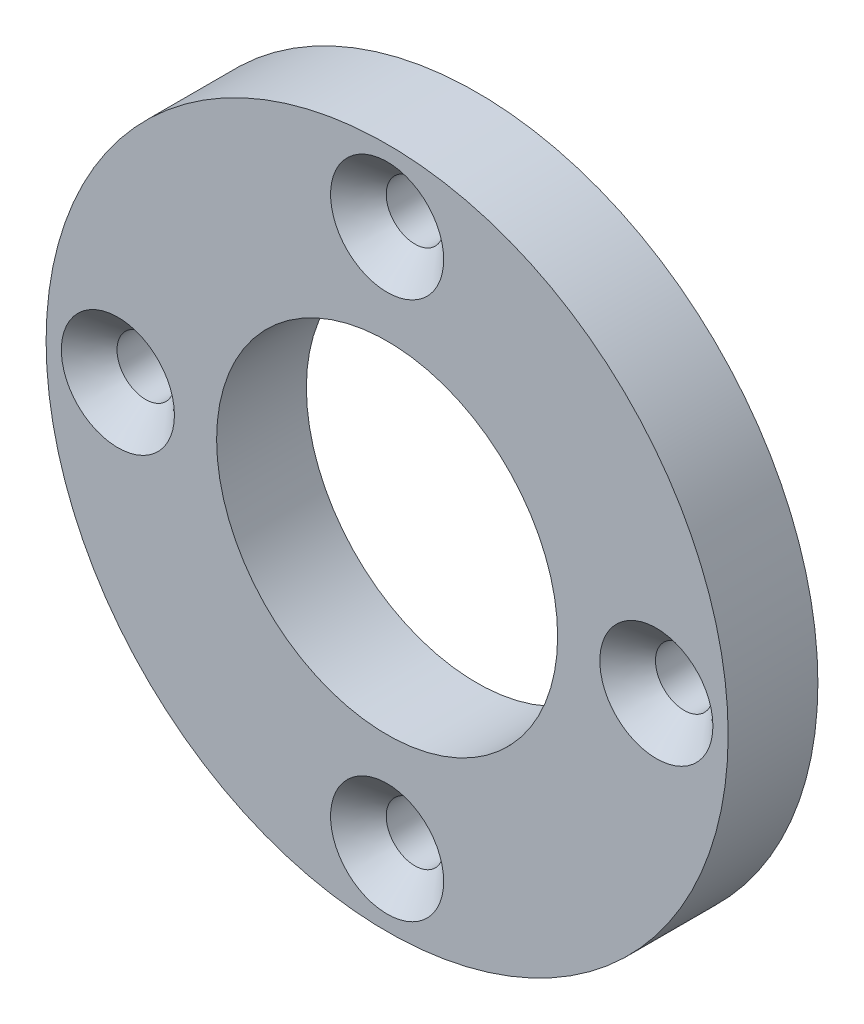
SolidWorks part; units mm, degrees
material "3.1325 (EN-AW 2017A)"
ref_plane "正面" through (0, 0, 0) normal (0, 0, 1) x (1, 0, 0)
ref_plane "平面" through (0, 0, 0) normal (0, 1, 0) x (1, 0, 0)
ref_plane "右側面" through (0, 0, 0) normal (1, 0, 0) x (0, 0, -1)
sketch "ｽｹｯﾁ1" plane through (0, 0, 0) normal (0, 0, 1) x (1, 0, 0)
  circle A0 centre (0, 0) radius 19
  circle A1 centre (0, 0) radius 9.5
  circle A2 centre (0, 0) radius 15 construction
  point P3 (0, 15)
  point P9 (15, 0)
  point P10 (0, -15)
  point P11 (-15, 0)
  point P12 (0, 0)
  dimension "D1" = 38
  dimension "D2" = 19
  dimension "D3" = 30
  dimension "D4" = 4
extrude "ﾎﾞｽ - 押し出し1" add sketch "ｽｹｯﾁ1" along normal blind 5
hole_wizard "M3 丸皿ねじ用皿穴1" positions "3Dｽｹｯﾁ1" profile "ｽｹｯﾁ2" countersink size "M3" standard "JIS" end condition through all
sketch3d "3Dｽｹｯﾁ1"
  point P28 (0, 15, 5)
  point P30 (15, 0, 5)
  point P32 (0, -15, 5)
  point P34 (-15, 0, 5)
sketch "ｽｹｯﾁ2" plane through (0, 15, 5) normal (1, 0, 0) x (0, -1, 0)
  line L0 (0, 0) -> (0, 5)
  line L1 (0, 5) -> (1.6, 5)
  line L2 (1.6, 5) -> (1.6, 1.55)
  line L3 (1.6, 1.55) -> (3.15, 0)
  line L5 (3.15, 0) -> (0, 0)
  line L6 (-1.6, 1.55) -> (-3.15, 0) construction
  line L11 (0, -6.35) -> (0, 107.95) construction
  dimension "通し穴の直径" = 3.2
  dimension "通し穴の深さ" = 5
  dimension "表面の皿穴の直径" = 6.3
  dimension "表面の皿穴の角度" = 90
hole_wizard "M3x0.5 ねじ穴用ねじ下穴ﾄﾞﾘﾙ1" positions "3Dｽｹｯﾁ2" profile "ｽｹｯﾁ3" hole size "M3x0.5" standard "JIS"
sketch3d "3Dｽｹｯﾁ2"
  point P0 (0, 15, 0)
  point P2 (15, 0, 0)
  point P4 (0, -15, 0)
  point P6 (-15, 0, 0)
sketch "ｽｹｯﾁ3" plane through (0, 15, 0) normal (1, 0, 0) x (0, 1, 0)
  line L0 (0, 0) -> (0, 5)
  line L1 (0, 5) -> (1.25, 5)
  line L2 (1.25, 5) -> (1.25, 0)
  line L5 (1.25, 0) -> (0, 0)
  line L11 (0, -6.35) -> (0, 107.95) construction
  dimension "通し穴の直径" = 2.5
  dimension "通し穴の深さ" = 5
